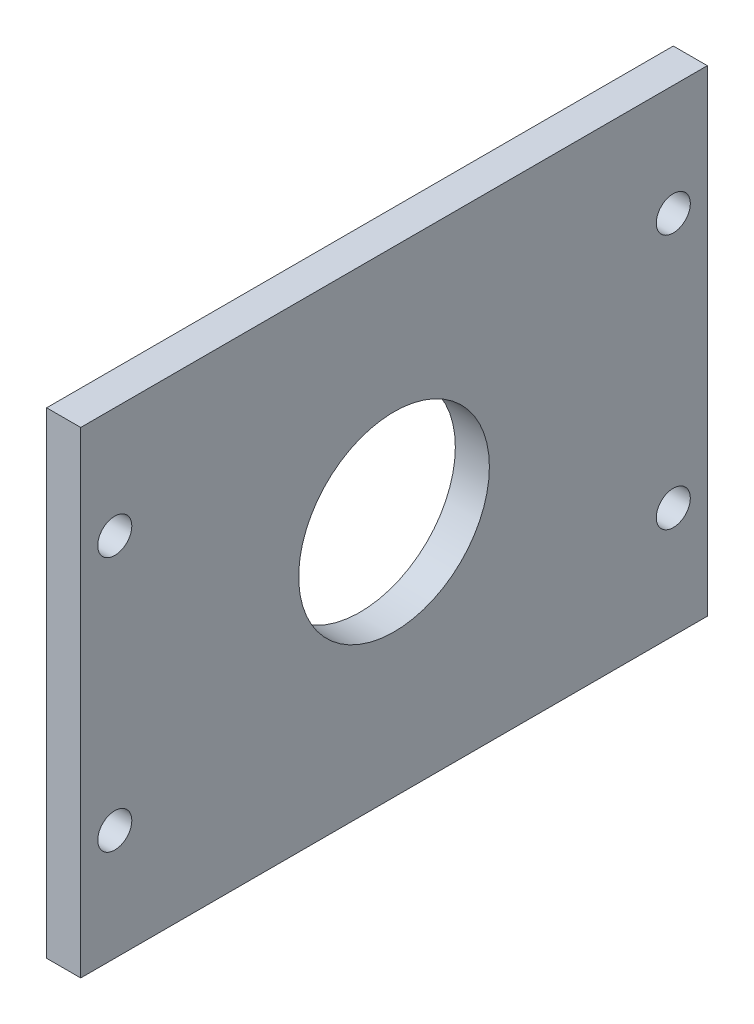
SolidWorks part; units mm, degrees
ref_plane "Front Plane" through (0, 0, 0) normal (0, 0, 1) x (1, 0, 0)
ref_plane "Top Plane" through (0, 0, 0) normal (0, 1, 0) x (1, 0, 0)
ref_plane "Right Plane" through (0, 0, 0) normal (1, 0, 0) x (0, 0, -1)
sketch "Sketch1" plane through (0, 0, 0) normal (1, 0, 0) x (0, 0, -1)
  line L0 (0, 0) -> (92, -70) construction
  line L1 (0, 0) -> (92, 0)
  line L2 (0, 0) -> (0, -70)
  line L3 (0, -70) -> (92, -70)
  line L4 (92, 0) -> (92, -70)
  line L5 (92, 0) -> (0, -70) construction
  line L6 (46, -35) -> (46, 0) construction
  line L7 (46, -17.5) -> (0, -17.5) construction
  circle A0 centre (46, -35) radius 14
  dimension "D3" = 28
  dimension "D1" = 70
  dimension "D2" = 92
extrude "Boss-Extrude1" add sketch "Sketch1" along normal blind 5
sketch "Sketch2" plane through (5, 0, 0) normal (1, 0, 0) x (0, 0, -1)
  line L0 (9.9892, 0) -> (9.9892, -70) construction
  line L1 (92, 0) -> (0, 0) construction
  line L2 (0, -70) -> (92, -70) construction
  line L3 (82.1061, 0) -> (82, -70) construction
  line L4 (82, 397) -> (82, -203) construction
  line L5 (9.9892, -35) -> (0, -35) construction
  line L6 (0, 0) -> (0, -70) construction
  line L7 (46, 0) -> (46, -70) construction
  circle A0 centre (5, -16.2724) radius 2.5
  circle A1 centre (5, -53.7276) radius 2.5
  circle A2 centre (87, -53.7276) radius 2.5
  circle A3 centre (87, -16.2724) radius 2.5
  dimension "D1" = 5
  dimension "D2" = 5
extrude "Cut-Extrude1" cut sketch "Sketch2" against normal through all both and the other way through all
